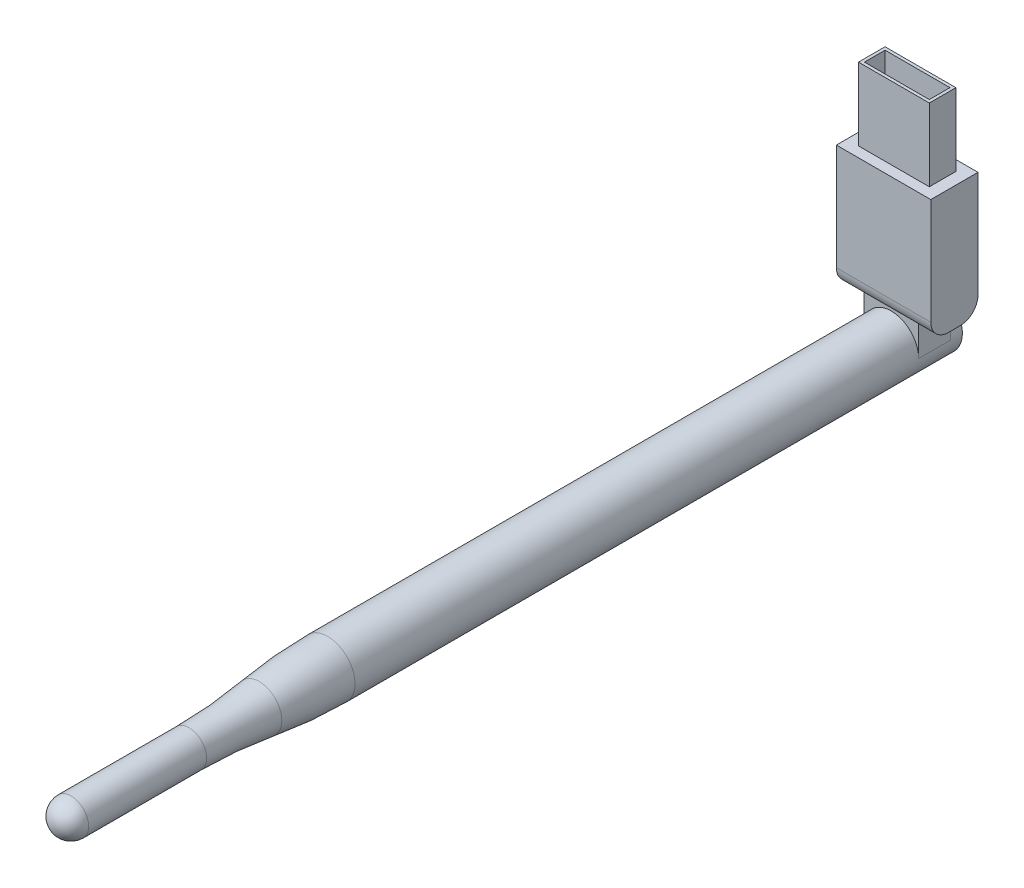
SolidWorks part; units mm, degrees
ref_plane "Frontal" through (0, 0, 0) normal (0, 0, 1) x (1, 0, 0)
ref_plane "Superior" through (0, 0, 0) normal (0, 1, 0) x (1, 0, 0)
ref_plane "Direito" through (0, 0, 0) normal (1, 0, 0) x (0, 0, -1)
sketch "Esboço1" plane through (0, 0, 0) normal (0, 0, 1) x (1, 0, 0)
  line L1 (-8, 10.5) -> (8, 10.5)
  line L2 (-8, 10.5) -> (-8, -10.5)
  line L3 (-8, -10.5) -> (8, -10.5)
  line L4 (8, 10.5) -> (8, -10.5)
  line L5 (-8, 10.5) -> (8, -10.5) construction
  line L6 (-8, -10.5) -> (8, 10.5) construction
  point P0 (0, 0)
extrude "Ressalto-extrusão1" add sketch "Esboço1" along normal blind 8
sketch "Esboço2" plane through (0, 10.5, 0) normal (0, 1, 0) x (1, 0, 0)
  line L0 (-8, -4) -> (8, -4) construction
  line L1 (-8, -8) -> (-8, 0) construction
  line L2 (8, -8) -> (8, 0) construction
  line L4 (-6, -1.75) -> (6, -1.75)
  line L5 (-6, -1.75) -> (-6, -6.25)
  line L6 (-6, -6.25) -> (6, -6.25)
  line L7 (6, -1.75) -> (6, -6.25)
  line L8 (-6, -1.75) -> (6, -6.25) construction
  line L9 (-6, -6.25) -> (6, -1.75) construction
  point P6 (0, -4)
extrude "Ressalto-extrusão2" add sketch "Esboço2" along normal blind 12.3
sketch "Esboço3" plane through (8, 0, 0) normal (1, 0, 0) x (0, 0, -1)
  line L1 (12.3021, -8.0412) -> (15.7598, -18.7093)
  line L2 (15.7598, -18.7093) -> (-12.8289, -20.2501)
  line L3 (-12.8289, -20.2501) -> (-17.7488, -20.2501)
  line L4 (0, -10.5) -> (0, 10.5)
  line L5 (0, 10.5) -> (-8, 10.5)
  line L6 (-8, 10.5) -> (-8, -10.5)
  line L7 (-8, -10.5) -> (0, -10.5)
  line L11 (-5, -10.5) -> (-3, -10.5)
  line L12 (0, -7.5) -> (12.3021, -8.0412)
  line L13 (-17.7488, -20.2501) -> (-21.5049, -7.0755)
  line L14 (-21.5049, -7.0755) -> (-8, -7.5)
  arc A0 (-8, -7.5) -> (-5, -10.5) centre (-5, -7.5) ccw
  arc A1 (0, -7.5) -> (-3, -10.5) centre (-3, -7.5) cw
  dimension "D2" = 3
  dimension "D1" = 0
extrude "Corte-extrusão1" cut sketch "Esboço3" against normal through all
sketch "Esboço4" plane through (0, -10.5, 0) normal (0, -1, 0) x (1, 0, 0)
  line L0 (0, 3) -> (0, 5) construction
  line L1 (-8, 3) -> (8, 3) construction
  line L2 (-8, 5) -> (8, 5) construction
  line L4 (-4.65, 6.7) -> (4.65, 6.7)
  line L5 (-4.65, 6.7) -> (-4.65, 1.3)
  line L6 (-4.65, 1.3) -> (4.65, 1.3)
  line L7 (4.65, 6.7) -> (4.65, 1.3)
  line L8 (-4.65, 6.7) -> (4.65, 1.3) construction
  line L9 (-4.65, 1.3) -> (4.65, 6.7) construction
  point P6 (0, 4)
extrude "Ressalto-extrusão3" add sketch "Esboço4" along normal blind 9.3 and the other way blind 12.3
sketch "Esboço8" plane through (0, 0, 0) normal (1, 0, 0) x (0, 0, -1)
  line L0 (-1.3, -15.15) -> (0.7, -15.15)
  line L1 (-6.7, -9.9718) -> (-6.7, -19.8) construction
  line L2 (-6.7, -15.15) -> (-148.7, -15.15)
  line L3 (-6.7, -15.15) -> (-1.3, -15.15)
  line L4 (0.7, -15.15) -> (0.7, -19.8)
  line L5 (0.7, -19.8) -> (-6.7, -19.8)
  line L6 (-6.7, -19.8) -> (-102.2062, -19.8)
  line L7 (-125.7, -15.15) -> (-125.7, -18.15) construction
  line L9 (-145.7, -18.15) -> (-125.7, -18.15)
  arc A0 (-102.2062, -19.8) -> (-113.8037, -18.9855) centre (-102.2062, 63.1729) cw
  arc A1 (-148.7, -15.15) -> (-145.7, -18.15) centre (-145.7, -15.15) ccw
  arc A2 (-113.8037, -18.9855) -> (-125.7, -18.15) centre (-125.7, -103.2616) ccw
  dimension "D4" = 6
  dimension "D5" = 5.4
  dimension "D1" = 2
  dimension "D2" = 142
  dimension "D3" = 4.65
  dimension "D6" = 95.5062
  dimension "D7" = 20
  dimension "D8" = 4.65
revolve "Revolução1" add sketch "Esboço8" angle 360 about L2
sketch "Esboço9" plane through (0, 0, 6.7) normal (0, 0, 1) x (1, 0, 0)
  line L0 (0, -19.8) -> (4.65, -19.8) construction
  line L1 (4.65, -19.8) -> (4.65, -15.15) construction
  line L2 (-4.65, -15.15) -> (-4.65, -19.8) construction
  line L3 (-4.65, -19.8) -> (0, -19.8) construction
  line L4 (0, -19.8) -> (4.65, -19.8)
  line L5 (4.65, -19.8) -> (4.65, -15.15)
  line L6 (-4.65, -15.15) -> (-4.65, -19.8)
  line L7 (-4.65, -19.8) -> (0, -19.8)
  arc A0 (0, -19.8) -> (4.65, -15.15) centre (0, -15.15) ccw construction
  arc A1 (-4.65, -15.15) -> (0, -19.8) centre (0, -15.15) ccw construction
  arc A2 (0, -19.8) -> (4.65, -15.15) centre (0, -15.15) ccw
  arc A3 (-4.65, -15.15) -> (0, -19.8) centre (0, -15.15) ccw
extrude "Corte-extrusão2" cut sketch "Esboço9" against normal through all contours A3 L6 L7
sketch "Esboço10" plane through (0, 10.5, 0) normal (0, 1, 0) x (1, 0, 0)
  line L0 (5.5, -5.75) -> (5.5, -2.25)
  line L1 (5.5, -2.25) -> (-5.5, -2.25)
  line L2 (-5.5, -2.25) -> (-5.5, -5.75)
  line L3 (-5.5, -5.75) -> (5.5, -5.75)
  line L4 (6, -6.25) -> (6, -1.75)
  line L5 (6, -1.75) -> (-6, -1.75)
  line L6 (-6, -1.75) -> (-6, -6.25)
  line L7 (-6, -6.25) -> (6, -6.25)
  line L8 (6, -6.25) -> (6, -1.75) construction
  line L9 (6, -1.75) -> (-6, -1.75) construction
  line L10 (-6, -1.75) -> (-6, -6.25) construction
  line L11 (-6, -6.25) -> (6, -6.25) construction
  dimension "D1" = 0
extrude "Corte-extrusão5" cut sketch "Esboço10" along normal through all from offset 3.75
